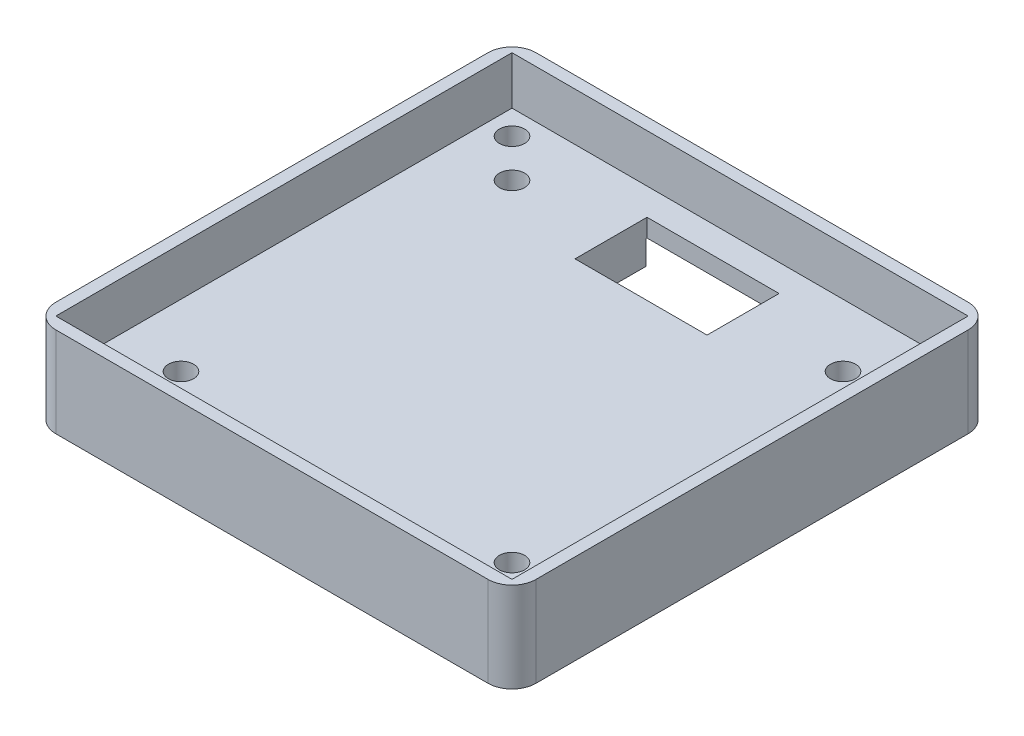
SolidWorks part; units mm, degrees
ref_plane "Front Plane" through (0, 0, 0) normal (0, 0, 1) x (1, 0, 0)
ref_plane "Top Plane" through (0, 0, 0) normal (0, 1, 0) x (1, 0, 0)
ref_plane "Right Plane" through (0, 0, 0) normal (1, 0, 0) x (0, 0, -1)
sketch "Sketch1" plane through (0, 0, 0) normal (0, 1, 0) x (1, 0, 0)
  line L1 (-20, 20) -> (20, 20)
  line L2 (-20, 20) -> (-20, -20)
  line L3 (-20, -20) -> (20, -20)
  line L4 (20, 20) -> (20, -20)
  line L5 (-20, 20) -> (20, -20) construction
  line L6 (-20, -20) -> (20, 20) construction
  point P0 (0, 0)
  dimension "D1" = 40
  dimension "D2" = 40
extrude "Boss-Extrude1" add sketch "Sketch1" along normal blind 3.5
sketch "Sketch2" plane through (0, 3.5, 0) normal (0, 1, 0) x (1, 0, 0)
  line L0 (-16.9706, 16.9706) -> (16.9706, -16.9706) construction
  line L1 (-19, 19) -> (19, 19) construction
  line L2 (-19, 19) -> (-19, -19) construction
  line L3 (-19, -19) -> (19, -19) construction
  line L4 (19, 19) -> (19, -19) construction
  line L5 (-19, 19) -> (19, -19) construction
  line L6 (-19, -19) -> (19, 19) construction
  line L7 (-16.9706, -16.9706) -> (16.9706, 16.9706) construction
  line L8 (-13.7886, -13.7886) -> (13.7886, 13.7886) construction
  line L9 (-13.7886, 13.7886) -> (13.7886, -13.7886) construction
  circle A0 centre (-16.9706, 16.9706) radius 1.05
  circle A1 centre (16.9706, 16.9706) radius 1.05
  circle A2 centre (-16.9706, -16.9706) radius 1.05
  circle A3 centre (16.9706, -16.9706) radius 1.05
  circle A4 centre (-13.7886, 13.7886) radius 1.05
  circle A5 centre (13.7886, 13.7886) radius 1.05
  circle A6 centre (13.7886, -13.7886) radius 1.05
  circle A7 centre (-13.7886, -13.7886) radius 1.05
  point P0 (0, 0)
  point P9 (0, 0)
  point P12 (0, 0)
  point P15 (0, 0)
  point P18 (0, 0)
  dimension "D7" = 2.1
  dimension "D1" = 38
  dimension "D2" = 38
  dimension "D3" = 48
  dimension "D4" = 48
  dimension "D5" = 39
  dimension "D6" = 39
extrude "Cut-Extrude1" cut sketch "Sketch2" against normal blind 3.5
sketch "Sketch3" plane through (0, 3.5, 0) normal (0, 1, 0) x (1, 0, 0)
  line L1 (-20, 20) -> (20, 20)
  line L2 (-20, 20) -> (-20, -20)
  line L3 (-20, -20) -> (20, -20)
  line L4 (20, 20) -> (20, -20)
  line L5 (-20, 20) -> (20, -20) construction
  line L6 (-20, -20) -> (20, 20) construction
  line L7 (-19, 19) -> (19, 19)
  line L8 (-19, 19) -> (-19, -19)
  line L9 (-19, -19) -> (19, -19)
  line L10 (19, 19) -> (19, -19)
  line L11 (-19, 19) -> (19, -19) construction
  line L12 (-19, -19) -> (19, 19) construction
  point P0 (0, 0)
  point P7 (0, 0)
  dimension "D1" = 38
  dimension "D2" = 38
extrude "Boss-Extrude2" add sketch "Sketch3" along normal blind 5
fillet "Fillet1" radius 2 4 edges at (20, 4.25, -20) (20, 4.25, 20) (-20, 4.25, 20) (-20, 4.25, -20)
sketch "Sketch4" plane through (0, 3.5, 0) normal (0, 1, 0) x (1, 0, 0)
  line L1 (-15.75, 15.75) -> (15.75, 15.75) construction
  line L2 (-15.75, 15.75) -> (-15.75, -15.75) construction
  line L3 (-15.75, -15.75) -> (15.75, -15.75) construction
  line L4 (15.75, 15.75) -> (15.75, -15.75) construction
  line L5 (-15.75, 15.75) -> (15.75, -15.75) construction
  line L6 (-15.75, -15.75) -> (15.75, 15.75) construction
  line L8 (0, 16.75) -> (-7.3335, 16.75) construction
  line L10 (-5.5, 16.75) -> (5.5, 16.75)
  line L11 (-5.5, 16.75) -> (-5.5, 10.75)
  line L12 (-5.5, 10.75) -> (5.5, 10.75)
  line L13 (5.5, 16.75) -> (5.5, 10.75)
  point P0 (0, 0)
  point P16 (0, 16.75)
  dimension "D1" = 31.5
  dimension "D2" = 31.5
  dimension "D3" = 1
  dimension "D4" = 11
  dimension "D5" = 6
extrude "Cut-Extrude2" cut sketch "Sketch4" against normal blind 5
sketch "Sketch5" plane through (0, 0, 0) normal (0, -1, 0) x (1, 0, 0)
  line L1 (-7.81, 18.511) -> (7.81, 18.511)
  line L2 (-10.81, 15.511) -> (-10.81, -16.689)
  line L3 (-7.81, -19.689) -> (7.81, -19.689)
  line L4 (10.81, 15.511) -> (10.81, -16.689)
  line L5 (-7.95, 15.711) -> (7.95, 15.711)
  line L6 (-7.95, 15.711) -> (-7.95, -16.679)
  line L7 (-7.95, -16.679) -> (7.95, -16.679)
  line L8 (7.95, 15.711) -> (7.95, -16.679)
  arc A0 (7.81, 18.511) -> (10.81, 15.511) centre (7.81, 15.511) cw
  arc A1 (10.81, -16.689) -> (7.81, -19.689) centre (7.81, -16.689) cw
  arc A2 (-7.81, -19.689) -> (-10.81, -16.689) centre (-7.81, -16.689) cw
  arc A3 (-7.81, 18.511) -> (-10.81, 15.511) centre (-7.81, 15.511) ccw
  point P0 (0, 0)
  point P6 (0, 0)
  point P7 (0, 18.511)
  point P14 (0, 15.711)
  point P17 (10.81, 18.511)
  point P22 (-10.81, -19.689)
  point P25 (-10.81, 18.511)
  dimension "D5" = 2.8
  dimension "D6" = 3.01
  dimension "D8" = 3
  dimension "D1" = 21.62
  dimension "D2" = 38.2
  dimension "D3" = 15.9
  dimension "D4" = 32.39
  dimension "D7" = 2.86
extrude "Cut-Extrude7" cut sketch "Sketch5" against normal blind 2
sketch "Sketch7" plane through (0, 8.5, 0) normal (0, 1, 0) x (1, 0, 0)
  line L1 (-21.7841, 21.5483) -> (21.7841, 21.5483)
  line L2 (-21.7841, 21.5483) -> (-21.7841, -21.5483)
  line L3 (-21.7841, -21.5483) -> (21.7841, -21.5483)
  line L4 (21.7841, 21.5483) -> (21.7841, -21.5483)
  line L5 (-21.7841, 21.5483) -> (21.7841, -21.5483) construction
  line L6 (-21.7841, -21.5483) -> (21.7841, 21.5483) construction
  point P0 (0, 0)
extrude "Cut-Extrude9" cut sketch "Sketch7" against normal blind 1
